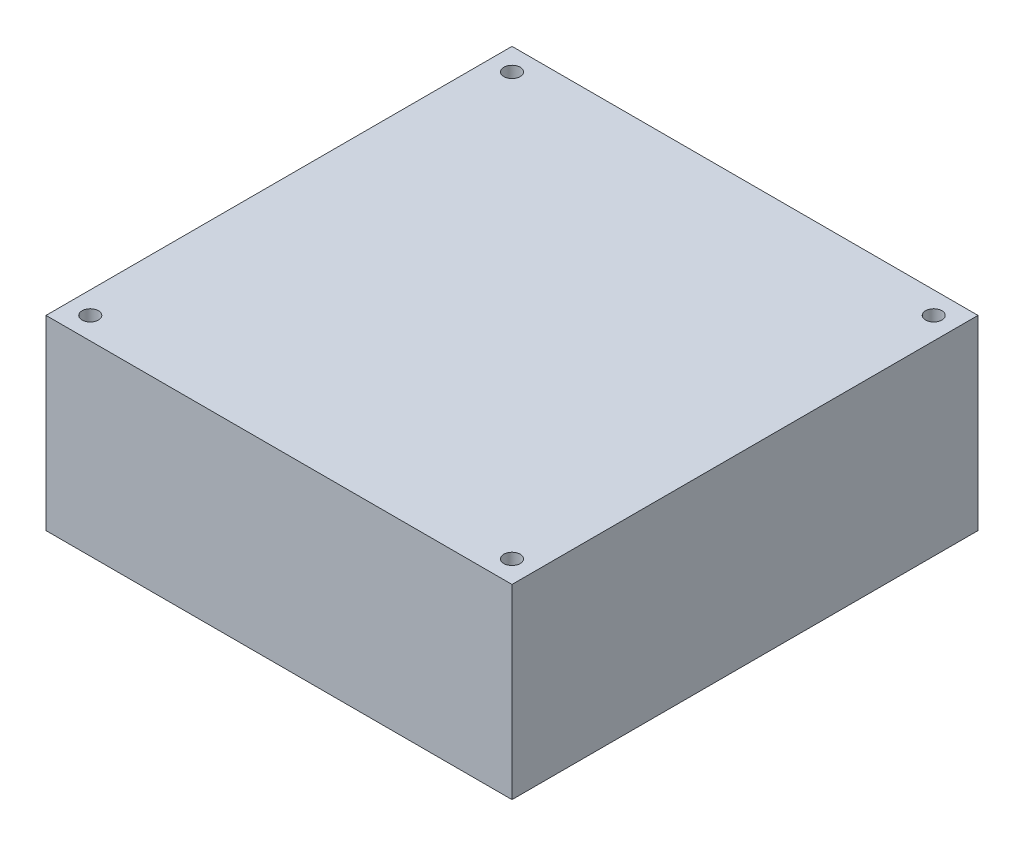
SolidWorks part; units mm, degrees
ref_plane "Plano frontal" through (0, 0, 0) normal (0, 0, 1) x (1, 0, 0)
ref_plane "Plano superior" through (0, 0, 0) normal (0, 1, 0) x (1, 0, 0)
ref_plane "Plano direito" through (0, 0, 0) normal (1, 0, 0) x (0, 0, -1)
ref_plane "Plano1" through (0, 40, 0) normal (0, 1, 0) x (1, 0, 0)
sketch "Esboço1" plane through (0, 40, 0) normal (0, 1, 0) x (1, 0, 0)
  line L0 (0, 100) -> (0, 0)
  line L1 (0, 0) -> (100, 0)
  line L2 (100, 0) -> (100, 100)
  line L3 (100, 100) -> (0, 100)
  circle A0 centre (4.75, 95.25) radius 1.75
  circle A1 centre (95.25, 95.25) radius 1.75
  circle A2 centre (95.25, 4.75) radius 1.75
  circle A3 centre (4.75, 4.75) radius 1.75
extrude "Ressalto-extrusão1" add sketch "Esboço1" against normal blind 40
